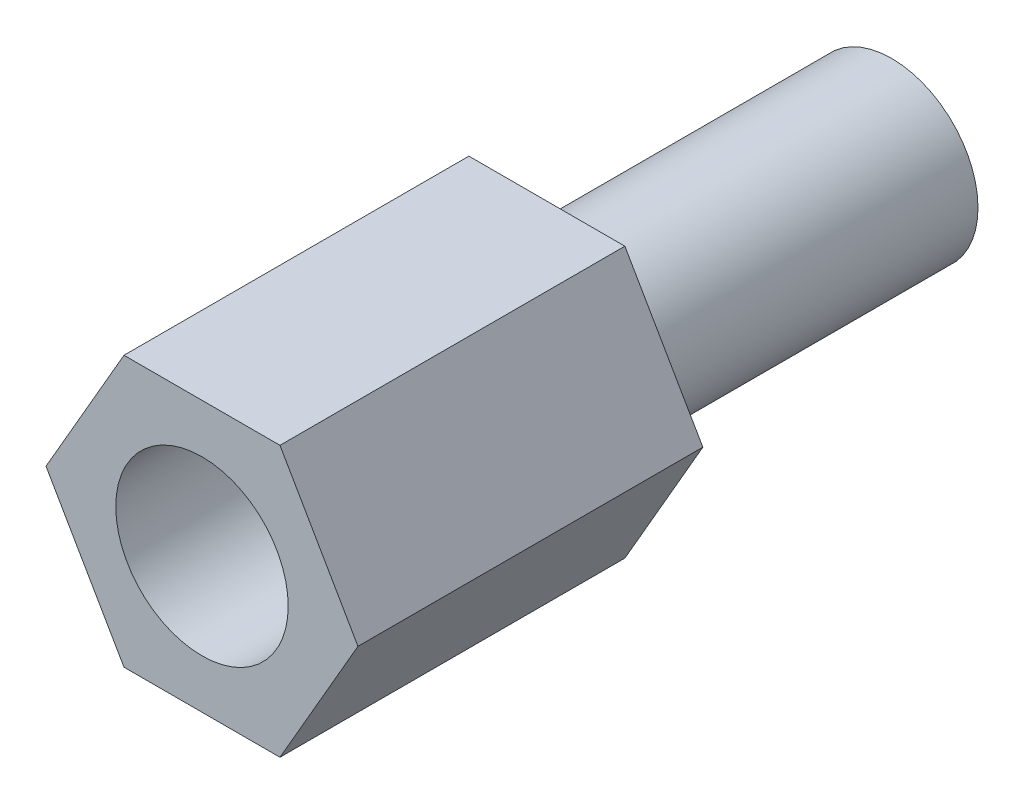
SolidWorks part; units mm, degrees
ref_plane "前视基准面" through (0, 0, 0) normal (0, 0, 1) x (1, 0, 0)
ref_plane "上视基准面" through (0, 0, 0) normal (0, 1, 0) x (1, 0, 0)
ref_plane "右视基准面" through (0, 0, 0) normal (1, 0, 0) x (0, 0, -1)
sketch "草图1" plane through (0, 0, 0) normal (0, 0, 1) x (1, 0, 0)
  line L1 (2.7135, 0) -> (1.3568, 2.35)
  line L2 (1.3568, 2.35) -> (-1.3568, 2.35)
  line L3 (-1.3568, 2.35) -> (-2.7135, 0)
  line L4 (-2.7135, 0) -> (-1.3568, -2.35)
  line L5 (-1.3568, -2.35) -> (1.3568, -2.35)
  line L6 (1.3568, -2.35) -> (2.7135, 0)
  circle A0 centre (0, 0) radius 2.35 construction
  dimension "D1" = 4.7
extrude "凸台-拉伸1" add sketch "草图1" against normal blind 6
sketch "草图2" plane through (0, 0, 0) normal (0, 0, 1) x (1, 0, 0)
  circle A0 centre (0, 0) radius 1.5
  dimension "D1" = 3
extrude "切除-拉伸1" cut sketch "草图2" against normal blind 3
sketch "草图3" plane through (0, 0, -6) normal (0, 0, -1) x (-1, 0, 0)
  circle A0 centre (0, 0) radius 1.5
  dimension "D1" = 3
extrude "凸台-拉伸2" add sketch "草图3" along normal blind 6
